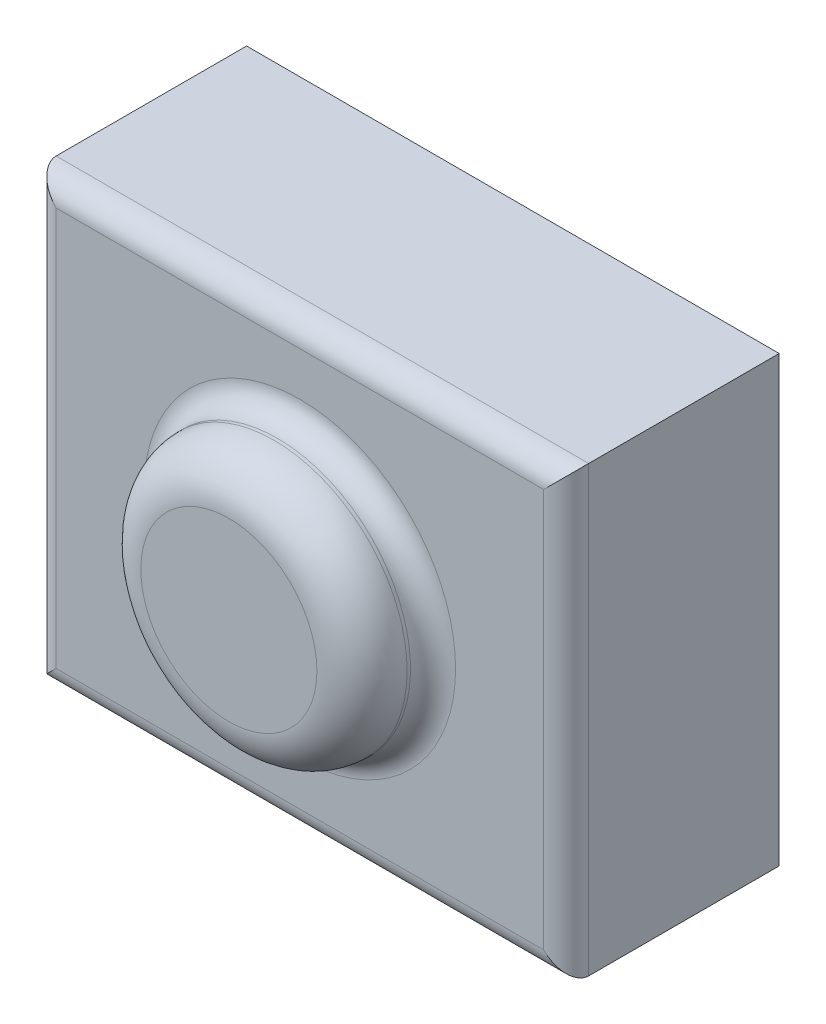
SolidWorks part; units mm, degrees
ref_plane "Front Plane" through (0, 0, 0) normal (0, 0, 1) x (1, 0, 0)
ref_plane "Top Plane" through (0, 0, 0) normal (0, 1, 0) x (1, 0, 0)
ref_plane "Right Plane" through (0, 0, 0) normal (1, 0, 0) x (0, 0, -1)
sketch "Sketch1" plane through (0, 0, 0) normal (0, 0, 1) x (1, 0, 0)
  line L1 (-1.5, -1.25) -> (1.5, -1.25)
  line L2 (-1.5, -1.25) -> (-1.5, 1.25)
  line L3 (-1.5, 1.25) -> (1.5, 1.25)
  line L4 (1.5, -1.25) -> (1.5, 1.25)
  line L5 (-1.5, -1.25) -> (1.5, 1.25) construction
  line L6 (-1.5, 1.25) -> (1.5, -1.25) construction
  point P0 (0, 0)
  dimension "D1" = 3
  dimension "D2" = 2.5
extrude "Boss-Extrude1" add sketch "Sketch1" along normal blind 1.2
sketch "Sketch2" plane through (0, 0, 1.2) normal (0, 0, 1) x (1, 0, 0)
  circle A0 centre (0, 0) radius 0.75
  dimension "D1" = 1.5
extrude "Boss-Extrude2" add sketch "Sketch2" along normal blind 0.4
fillet "Fillet1" radius 0.254 1 edges at (0.75, 0, 1.6)
fillet "Fillet2" radius 0.127 5 edges at (-0.75, 0, 1.2) (0, -1.25, 1.2) (-1.5, 0, 1.2) (0, 1.25, 1.2) (1.5, 0, 1.2)
